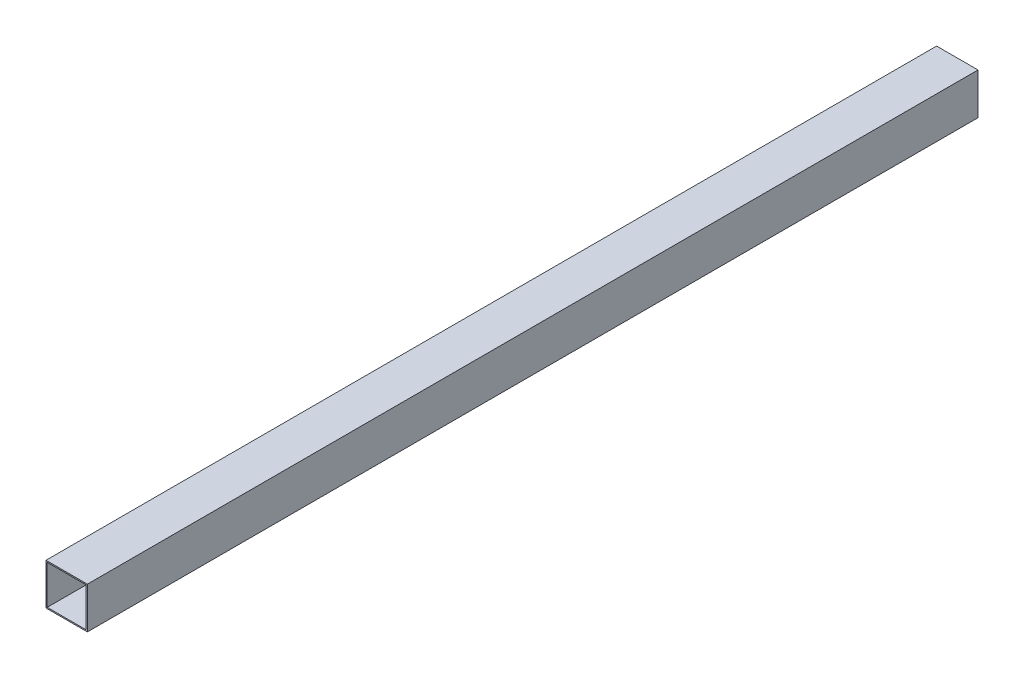
SolidWorks part; units mm, degrees
ref_plane "Front Plane" through (0, 0, 0) normal (0, 0, 1) x (1, 0, 0)
ref_plane "Top Plane" through (0, 0, 0) normal (0, 1, 0) x (1, 0, 0)
ref_plane "Right Plane" through (0, 0, 0) normal (1, 0, 0) x (0, 0, -1)
sketch "Sketch1" plane through (0, 0, 0) normal (0, 0, 1) x (1, 0, 0)
  line L0 (-40, -40) -> (-40, 40)
  line L1 (42.5, -42.5) -> (-42.5, -42.5)
  line L2 (42.5, -42.5) -> (42.5, 42.5)
  line L3 (42.5, 42.5) -> (-42.5, 42.5)
  line L4 (-42.5, -42.5) -> (-42.5, 42.5)
  line L5 (42.5, -42.5) -> (-42.5, 42.5) construction
  line L6 (42.5, 42.5) -> (-42.5, -42.5) construction
  line L7 (40, 40) -> (-40, 40)
  line L8 (40, -40) -> (40, 40)
  line L9 (40, -40) -> (-40, -40)
  point P0 (0, 0)
  dimension "D1" = 85
  dimension "D2" = 85
  dimension "D3" = 2.5
extrude "Boss-Extrude1" add sketch "Sketch1" along normal blind 1828.8
